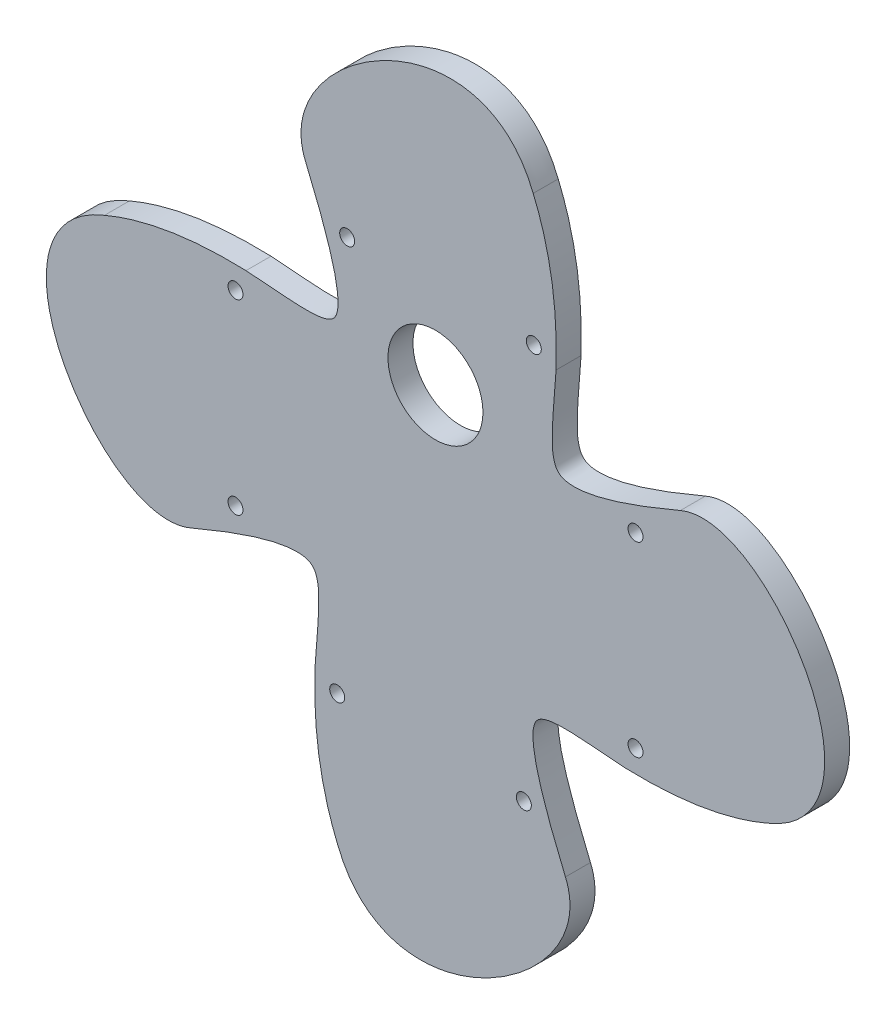
SolidWorks part; units mm, degrees
ref_plane "Front Plane" through (0, 0, 0) normal (0, 0, 1) x (1, 0, 0)
ref_plane "Top Plane" through (0, 0, 0) normal (0, 1, 0) x (1, 0, 0)
ref_plane "Right Plane" through (0, 0, 0) normal (1, 0, 0) x (0, 0, -1)
sketch "Sketch1" plane through (0, 0, 0) normal (0, 0, 1) x (1, 0, 0)
  line L0 (15.9859, 133.6591) -> (15.9859, 38.7698) construction
  line L5 (25.9859, 96.5039) -> (25.9859, 93.5039) construction
  line L6 (5.9859, 42.4646) -> (25.9859, 42.4646) construction
  line L7 (5.9859, 42.4646) -> (5.9859, 62.4646) construction
  line L8 (5.9859, 62.4646) -> (25.9859, 62.4646) construction
  line L9 (25.9859, 42.4646) -> (25.9859, 62.4646) construction
  line L10 (5.9859, 42.4646) -> (25.9859, 62.4646) construction
  line L11 (5.9859, 62.4646) -> (25.9859, 42.4646) construction
  line L16 (19.9859, 68.5146) -> (11.9859, 68.5146) construction
  line L17 (-26.0141, 70.6243) -> (-26.0141, 37.6243) construction
  line L18 (3.4859, 96.5039) -> (28.4859, 96.5039) construction
  line L19 (3.4859, 96.5039) -> (3.4859, 93.5039) construction
  line L20 (3.4859, 93.5039) -> (28.4859, 93.5039) construction
  line L21 (28.4859, 96.5039) -> (28.4859, 93.5039) construction
  line L22 (3.4859, 96.5039) -> (28.4859, 93.5039) construction
  line L23 (3.4859, 93.5039) -> (28.4859, 96.5039) construction
  line L24 (25.9859, 93.5039) -> (3.4859, 93.5039) construction
  line L25 (3.4859, 96.5039) -> (25.9859, 96.5039) construction
  line L26 (-0.5141, 93.5039) -> (32.4859, 93.5039) construction
  line L27 (-0.5141, 93.5039) -> (-0.5141, 125.5039) construction
  line L28 (-0.5141, 125.5039) -> (32.4859, 125.5039) construction
  line L29 (32.4859, 93.5039) -> (32.4859, 125.5039) construction
  line L30 (-0.5141, 93.5039) -> (32.4859, 125.5039) construction
  line L31 (-0.5141, 125.5039) -> (32.4859, 93.5039) construction
  line L32 (25.9859, 70.6243) -> (57.9859, 70.6243) construction
  line L33 (25.9859, 70.6243) -> (25.9859, 37.6243) construction
  line L34 (25.9859, 37.6243) -> (57.9859, 37.6243) construction
  line L35 (57.9859, 70.6243) -> (57.9859, 37.6243) construction
  line L36 (5.9859, 37.6243) -> (-26.0141, 37.6243) construction
  line L37 (5.9859, 70.6243) -> (5.9859, 37.6243) construction
  line L38 (5.9859, 70.6243) -> (-26.0141, 70.6243) construction
  circle A0 centre (15.9859, 82.5039) radius 9.5
  circle A4 centre (11.9859, 68.5146) radius 1.25 construction
  circle A5 centre (19.9859, 68.5146) radius 1.25 construction
  circle A6 centre (19.9859, 68.5146) radius 5.05 construction
  spline S0 degree 3 poles (16.8614, 61.071) (19.1525, 88.4527) (-4.5658, 100.1358) (-8.1539, 109.0166) knots 0 0 0 0 1 1 1 1 construction
  spline S1 degree 3 poles (-8.1539, 109.0166) (-14.7239, 124.1957) (23.9896, 149.4382) (33.6812, 124.7097) knots 0 0 0 0 1 1 1 1 construction
  spline S2 degree 3 poles (33.6812, 124.7097) (42.7198, 103.6961) (38.6714, 66.4651) (16.8614, 61.071) knots 0 0 0 0 1 1 1 1 construction
  spline S3 degree 3 poles (81.4407, 41.5775) (60.4271, 32.5389) (23.1961, 36.5873) (17.802, 58.3973) knots 0 0 0 0 1 1 1 1 construction
  spline S4 degree 3 poles (17.802, 58.3973) (45.1837, 56.1063) (56.8668, 79.8246) (65.7477, 83.4126) knots 0 0 0 0 1 1 1 1 construction
  spline S5 degree 3 poles (65.7477, 83.4126) (80.9267, 89.9827) (106.1692, 51.2692) (81.4407, 41.5775) knots 0 0 0 0 1 1 1 1 construction
  spline S6 degree 3 poles (-1.6915, -6.182) (-10.7301, 14.8316) (-6.6817, 52.0626) (15.1283, 57.4568) knots 0 0 0 0 1 1 1 1 construction
  spline S7 degree 3 poles (15.1283, 57.4568) (12.8373, 30.0751) (36.5556, 18.3919) (40.1436, 9.5111) knots 0 0 0 0 1 1 1 1 construction
  spline S8 degree 3 poles (40.1436, 9.5111) (46.7137, -5.668) (8.0002, -30.9104) (-1.6915, -6.182) knots 0 0 0 0 1 1 1 1 construction
  spline S9 degree 3 poles (-49.451, 76.9502) (-28.4374, 85.9888) (8.7936, 81.9404) (14.1878, 60.1304) knots 0 0 0 0 1 1 1 1 construction
  spline S10 degree 3 poles (14.1878, 60.1304) (-13.1939, 62.4215) (-24.8771, 38.7032) (-33.7579, 35.1151) knots 0 0 0 0 1 1 1 1 construction
  spline S11 degree 3 poles (-33.7579, 35.1151) (-48.937, 28.5451) (-74.1794, 67.2586) (-49.451, 76.9502) knots 0 0 0 0 1 1 1 1 construction
  spline S12 degree 3 poles (-8.1539, 109.0166) (5.8128, 76.0688) (-3.7824, 80.2696) (-21.9955, 81.376) knots 0 0 0 0 1 1 1 1 construction
  spline S13 degree 2 poles (-49.451, 76.9502) (-37.9198, 81.8915) (-21.9955, 81.376) knots 0 0 0 1 1 1 construction
  spline S14 degree 2 poles (33.6812, 124.7097) (38.6225, 113.1785) (38.107, 97.2542) knots 0 0 0 1 1 1 construction
  spline S15 degree 3 poles (65.7477, 83.4126) (32.7998, 69.446) (37.0006, 79.0411) (38.107, 97.2542) knots 0 0 0 0 1 1 1 1 construction
  spline S16 degree 2 poles (81.4407, 41.5775) (69.9096, 36.6362) (53.9852, 37.1517) knots 0 0 0 1 1 1 construction
  spline S17 degree 3 poles (40.1436, 9.5111) (26.177, 42.4589) (35.7722, 38.2582) (53.9852, 37.1517) knots 0 0 0 0 1 1 1 1 construction
  spline S18 degree 2 poles (-1.6915, -6.182) (-6.6328, 5.3492) (-6.1173, 21.2735) knots 0 0 0 1 1 1 construction
  spline S19 degree 3 poles (-33.7579, 35.1151) (-0.8101, 49.0817) (-5.0108, 39.4866) (-6.1173, 21.2735) knots 0 0 0 0 1 1 1 1 construction
  spline S20 degree 1 poles (-3.542, -6.9412) (-8.1153, 21.3665) knots 0 0 1 1 construction
  spline S21 degree 1 poles (-32.9708, 33.2765) (-8.1153, 21.3665) knots 0 0 1 1 construction
  spline S22 degree 1 poles (-32.9708, 33.2765) (-50.2102, 78.8007) knots 0 0 1 1 construction
  spline S23 degree 1 poles (-50.2102, 78.8007) (-21.9025, 83.3741) knots 0 0 1 1 construction
  spline S24 degree 1 poles (-9.9925, 108.2295) (-21.9025, 83.3741) knots 0 0 1 1 construction
  spline S25 degree 1 poles (-9.9925, 108.2295) (35.5317, 125.469) knots 0 0 1 1 construction
  spline S26 degree 1 poles (35.5317, 125.469) (40.1051, 97.1612) knots 0 0 1 1 construction
  spline S27 degree 1 poles (64.9605, 85.2512) (40.1051, 97.1612) knots 0 0 1 1 construction
  spline S28 degree 1 poles (64.9605, 85.2512) (82.2, 39.727) knots 0 0 1 1 construction
  spline S29 degree 1 poles (82.2, 39.727) (53.8922, 35.1537) knots 0 0 1 1 construction
  spline S30 degree 1 poles (41.9822, 10.2982) (53.8922, 35.1537) knots 0 0 1 1 construction
  spline S31 degree 1 poles (41.9822, 10.2982) (-3.542, -6.9412) knots 0 0 1 1 construction
  spline S32 degree 2 poles (-3.542, -6.9412) (-8.667, 5.1045) (-8.1153, 21.3665) knots 0.001185 0.001185 0.001185 1.000889 1.000889 1.000889
  spline S33 degree 3 poles (-8.1153, 21.3665) (-8.0808, 21.9348) (-8.0041, 23.0851) (-7.8384, 25.271) (-7.6232, 27.8547) (-7.4142, 30.6638) (-7.2734, 33.9809) (-7.4626, 36.563) (-8.03, 38.1615) (-8.5526, 38.8833) (-9.2308, 39.3726) (-10.4146, 39.7436) (-12.2957, 39.8323) (-14.8912, 39.5173) (-18.2102, 38.7418) (-21.5997, 37.6853) (-24.7056, 36.582) (-27.2365, 35.6235) (-29.5238, 34.711) (-31.4515, 33.9167) (-32.4695, 33.489) (-32.9708, 33.2765) knots 0.000067 0.000067 0.000067 0.000067 0.031331 0.062595 0.125123 0.187652 0.25018 0.375236 0.437764 0.500292 0.56282 0.625349 0.687877 0.750405 0.812933 0.875461 0.906725 0.937989 0.969253 0.984885 1.000517 1.000517 1.000517 1.000517
  spline S34 degree 3 poles (-32.9708, 33.2765) (-33.5431, 33.0293) (-34.7402, 32.6308) (-37.1706, 32.26) (-40.245, 32.5176) (-43.8292, 33.7656) (-48.4091, 36.4387) (-53.6534, 41.3427) (-58.6696, 48.875) (-61.2463, 55.8816) (-61.9576, 61.5623) (-61.6934, 65.7665) (-60.4936, 69.7927) (-58.61, 72.8489) (-56.548, 75.0101) (-54.7267, 76.4675) (-52.9768, 77.5338) (-51.4462, 78.2888) (-50.6218, 78.6388) (-50.2102, 78.8007) knots 0.000131 0.000131 0.000131 0.000131 0.031365 0.0626 0.125069 0.187538 0.250007 0.374945 0.499882 0.62482 0.687289 0.749758 0.812227 0.874696 0.905931 0.937165 0.9684 0.984017 0.999634 0.999634 0.999634 0.999634
  spline S35 degree 2 poles (-50.2102, 78.8007) (-38.1645, 83.9257) (-21.9025, 83.3741) knots 0.001185 0.001185 0.001185 1.000889 1.000889 1.000889
  spline S36 degree 3 poles (-21.9025, 83.3741) (-21.3342, 83.3395) (-20.1839, 83.2629) (-17.998, 83.0971) (-15.4143, 82.882) (-12.6052, 82.6729) (-9.2881, 82.5321) (-6.706, 82.7214) (-5.1075, 83.2888) (-4.3857, 83.8114) (-3.8964, 84.4895) (-3.5254, 85.6733) (-3.4367, 87.5545) (-3.7516, 90.15) (-4.5272, 93.469) (-5.5837, 96.8584) (-6.687, 99.9644) (-7.6455, 102.4952) (-8.558, 104.7826) (-9.3523, 106.7102) (-9.78, 107.7283) (-9.9925, 108.2295) knots 0.000067 0.000067 0.000067 0.000067 0.031331 0.062595 0.125123 0.187652 0.25018 0.375236 0.437764 0.500292 0.56282 0.625349 0.687877 0.750405 0.812933 0.875461 0.906725 0.937989 0.969253 0.984885 1.000517 1.000517 1.000517 1.000517
  spline S37 degree 3 poles (-9.9925, 108.2295) (-10.2397, 108.8018) (-10.6382, 109.999) (-11.009, 112.4293) (-10.7514, 115.5038) (-9.5034, 119.0879) (-6.8302, 123.6679) (-1.9263, 128.9121) (5.606, 133.9284) (12.6126, 136.505) (18.2933, 137.2164) (22.4975, 136.9521) (26.5237, 135.7524) (29.5799, 133.8688) (31.7411, 131.8068) (33.1985, 129.9855) (34.2648, 128.2355) (35.0198, 126.7049) (35.3698, 125.8805) (35.5317, 125.469) knots 0.000131 0.000131 0.000131 0.000131 0.031365 0.0626 0.125069 0.187538 0.250007 0.374945 0.499882 0.62482 0.687289 0.749758 0.812227 0.874696 0.905931 0.937165 0.9684 0.984017 0.999634 0.999634 0.999634 0.999634
  spline S38 degree 2 poles (35.5317, 125.469) (40.6567, 113.4233) (40.1051, 97.1612) knots 0.001185 0.001185 0.001185 1.000889 1.000889 1.000889
  spline S39 degree 3 poles (40.1051, 97.1612) (40.0706, 96.5929) (39.9939, 95.4427) (39.8281, 93.2567) (39.613, 90.6731) (39.404, 87.8639) (39.2632, 84.5468) (39.4524, 81.9648) (40.0198, 80.3662) (40.5424, 79.6444) (41.2205, 79.1551) (42.4043, 78.7842) (44.2855, 78.6954) (46.881, 79.0104) (50.2, 79.7859) (53.5894, 80.8424) (56.6954, 81.9457) (59.2262, 82.9042) (61.5136, 83.8168) (63.4412, 84.611) (64.4593, 85.0388) (64.9605, 85.2512) knots 0.000067 0.000067 0.000067 0.000067 0.031331 0.062595 0.125123 0.187652 0.25018 0.375236 0.437764 0.500292 0.56282 0.625349 0.687877 0.750405 0.812933 0.875461 0.906725 0.937989 0.969253 0.984885 1.000517 1.000517 1.000517 1.000517
  spline S40 degree 3 poles (64.9605, 85.2512) (65.5328, 85.4985) (66.73, 85.8969) (69.1603, 86.2678) (72.2348, 86.0101) (75.8189, 84.7621) (80.3989, 82.089) (85.6432, 77.1851) (90.6594, 69.6528) (93.236, 62.6461) (93.9474, 56.9654) (93.6831, 52.7613) (92.4834, 48.735) (90.5998, 45.6788) (88.5378, 43.5177) (86.7165, 42.0602) (84.9665, 40.9939) (83.4359, 40.2389) (82.6115, 39.8889) (82.2, 39.727) knots 0.000131 0.000131 0.000131 0.000131 0.031365 0.0626 0.125069 0.187538 0.250007 0.374945 0.499882 0.62482 0.687289 0.749758 0.812227 0.874696 0.905931 0.937165 0.9684 0.984017 0.999634 0.999634 0.999634 0.999634
  spline S41 degree 2 poles (82.2, 39.727) (70.1543, 34.602) (53.8922, 35.1537) knots 0.001185 0.001185 0.001185 1.000889 1.000889 1.000889
  spline S42 degree 3 poles (53.8922, 35.1537) (53.324, 35.1882) (52.1737, 35.2649) (49.9877, 35.4306) (47.4041, 35.6458) (44.5949, 35.8548) (41.2778, 35.9956) (38.6958, 35.8064) (37.0972, 35.239) (36.3754, 34.7163) (35.8861, 34.0382) (35.5152, 32.8544) (35.4265, 30.9732) (35.7414, 28.3778) (36.5169, 25.0588) (37.5734, 21.6693) (38.6767, 18.5634) (39.6352, 16.0325) (40.5478, 13.7452) (41.342, 11.8175) (41.7698, 10.7995) (41.9822, 10.2982) knots 0.000067 0.000067 0.000067 0.000067 0.031331 0.062595 0.125123 0.187652 0.25018 0.375236 0.437764 0.500292 0.56282 0.625349 0.687877 0.750405 0.812933 0.875461 0.906725 0.937989 0.969253 0.984885 1.000517 1.000517 1.000517 1.000517
  spline S43 degree 3 poles (41.9822, 10.2982) (42.2295, 9.7259) (42.6279, 8.5288) (42.9988, 6.0984) (42.7411, 3.024) (41.4931, -0.5602) (38.82, -5.1401) (33.9161, -10.3844) (26.3838, -15.4006) (19.3771, -17.9773) (13.6965, -18.6886) (9.4923, -18.4244) (5.466, -17.2246) (2.4098, -15.341) (0.2487, -13.279) (-1.2087, -11.4577) (-2.2751, -9.7078) (-3.0301, -8.1772) (-3.3801, -7.3528) (-3.542, -6.9412) knots 0.000131 0.000131 0.000131 0.000131 0.031365 0.0626 0.125069 0.187538 0.250007 0.374945 0.499882 0.62482 0.687289 0.749758 0.812227 0.874696 0.905931 0.937165 0.9684 0.984017 0.999634 0.999634 0.999634 0.999634
  point P0 (15.9859, 52.4646)
  point P12 (19.9859, 63.4646)
  point P14 (15.9859, 109.5039)
  point P17 (15.9859, 95.0039)
  point P23 (15.9859, 73.0039)
  point P24 (15.9859, 92.0039)
  point P25 (15.9859, 68.5146)
  point P44 (15.9949, 59.2639)
  dimension "D1" = 19
  dimension "D5" = 2.5
  dimension "D7" = 3.8
  dimension "D2" = 25
  dimension "D3" = 10
  dimension "D4" = 3
  dimension "D6" = 8
  dimension "D8" = 1.5
  dimension "D9" = 1
  dimension "D10" = 20
  dimension "D11" = 20
  dimension "D12" = 32
  dimension "D13" = 33
  dimension "D14" = 33
  dimension "D15" = 32
  dimension "D16" = 2
extrude "Boss-Extrude1" add sketch "Sketch1" along normal blind 5
sketch "Sketch2" plane through (0, 0, 5) normal (0, 0, 1) x (1, 0, 0)
  line L0 (-50.2102, 78.8007) -> (82.2, 39.727) construction
  line L1 (-1.6711, 99.2639) -> (35.6529, 99.2639) construction
  line L2 (64.9605, 85.2512) -> (-32.9708, 33.2765) construction
  circle A0 centre (-1.6711, 99.2639) radius 1.5
  circle A1 centre (35.6529, 99.2639) radius 1.5
  circle A2 centre (-1.6711, 99.2639) radius 4.5 construction
  circle A3 centre (35.6529, 99.2639) radius 4.5 construction
  circle A10 centre (55.9949, 39.6059) radius 1.5
  circle A11 centre (55.9949, 76.9298) radius 1.5
  circle A12 centre (-3.6631, 19.2639) radius 1.5
  circle A13 centre (33.6608, 19.2639) radius 1.5
  circle A14 centre (-24.0051, 78.9219) radius 1.5
  circle A15 centre (-24.0051, 41.5979) radius 1.5
  parabola Q0 (40.1051, 97.1612) -> (35.5317, 125.469) focus (11.6295, 121.4725) apex (30.0153, 135.1288) construction
  parabola Q15 (40.1051, 97.1612) -> (35.5317, 125.469) focus (11.6295, 121.4725) apex (30.0153, 135.1288) construction
  parabola Q16 (40.1051, 97.1612) -> (35.5317, 125.469) focus (11.6295, 121.4725) apex (30.0153, 135.1288) construction
  spline S0 degree 3 poles (-9.9925, 108.2295) (-9.78, 107.7283) (-9.3523, 106.7102) (-8.558, 104.7826) (-7.6455, 102.4952) (-6.687, 99.9644) (-5.5837, 96.8584) (-4.5272, 93.469) (-3.7516, 90.15) (-3.4367, 87.5545) (-3.5254, 85.6733) (-3.8964, 84.4895) (-4.3857, 83.8114) (-5.1075, 83.2888) (-6.706, 82.7214) (-9.2881, 82.5321) (-12.6052, 82.6729) (-15.4143, 82.882) (-17.998, 83.0971) (-20.1839, 83.2629) (-21.3342, 83.3395) (-21.9025, 83.3741) knots 0.000067 0.000067 0.000067 0.000067 0.015699 0.031331 0.062595 0.093859 0.125123 0.187652 0.25018 0.312708 0.375236 0.437764 0.500292 0.56282 0.625349 0.750405 0.812933 0.875461 0.937989 0.969253 1.000517 1.000517 1.000517 1.000517 construction
  point P0 (15.9949, 59.2639)
  point P4 (15.9949, 59.2639)
  point P30 (40.1529, 99.2639)
  dimension "D1" = 3
  dimension "D4" = 3
  dimension "D2" = 40
  dimension "D3" = 4
extrude "Cut-Extrude1" cut sketch "Sketch2" against normal up to next
